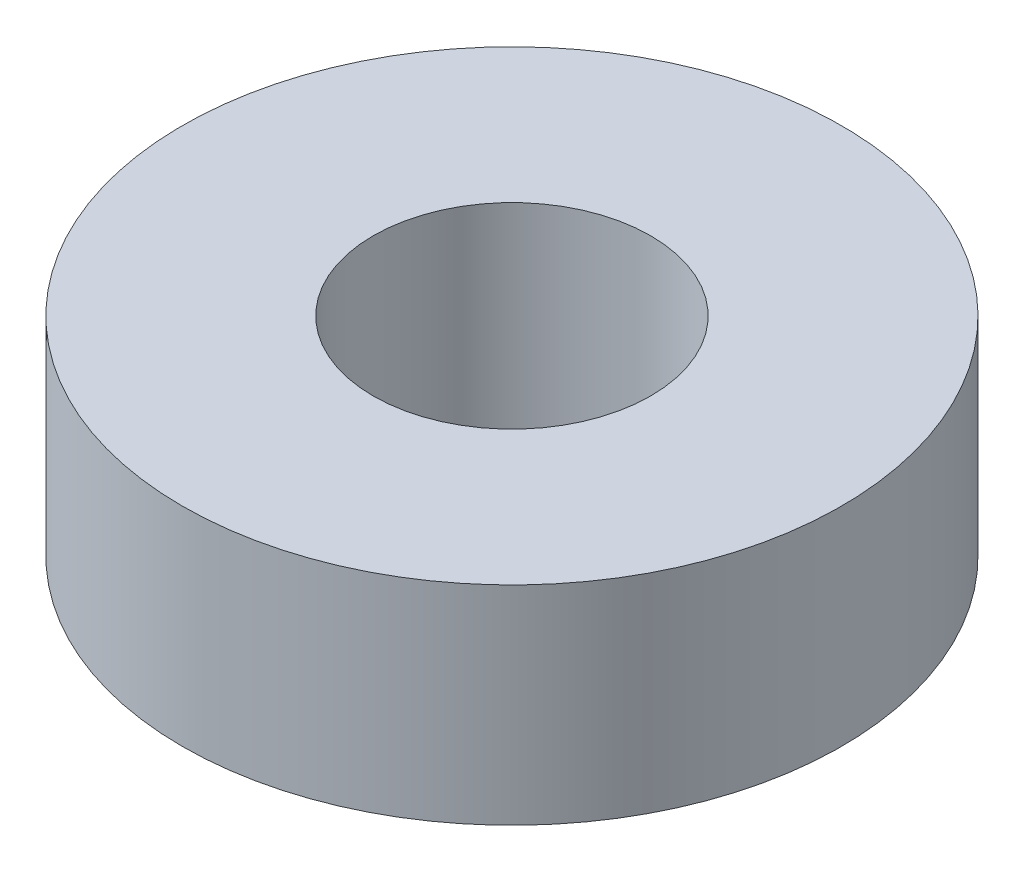
SolidWorks part; units mm, degrees
material "Molybdenum"
ref_plane "Front Plane" through (0, 0, 0) normal (0, 0, 1) x (1, 0, 0)
ref_plane "Top Plane" through (0, 0, 0) normal (0, 1, 0) x (1, 0, 0)
ref_plane "Right Plane" through (0, 0, 0) normal (1, 0, 0) x (0, 0, -1)
sketch "Sketch1" plane through (0, 0, 0) normal (0, 1, 0) x (1, 0, 0)
  circle A0 centre (0, 0) radius 4.75
  circle A1 centre (0, 0) radius 2
  dimension "D1" = 9.5
  dimension "D2" = 4
extrude "Boss-Extrude1" add sketch "Sketch1" along normal blind 3
